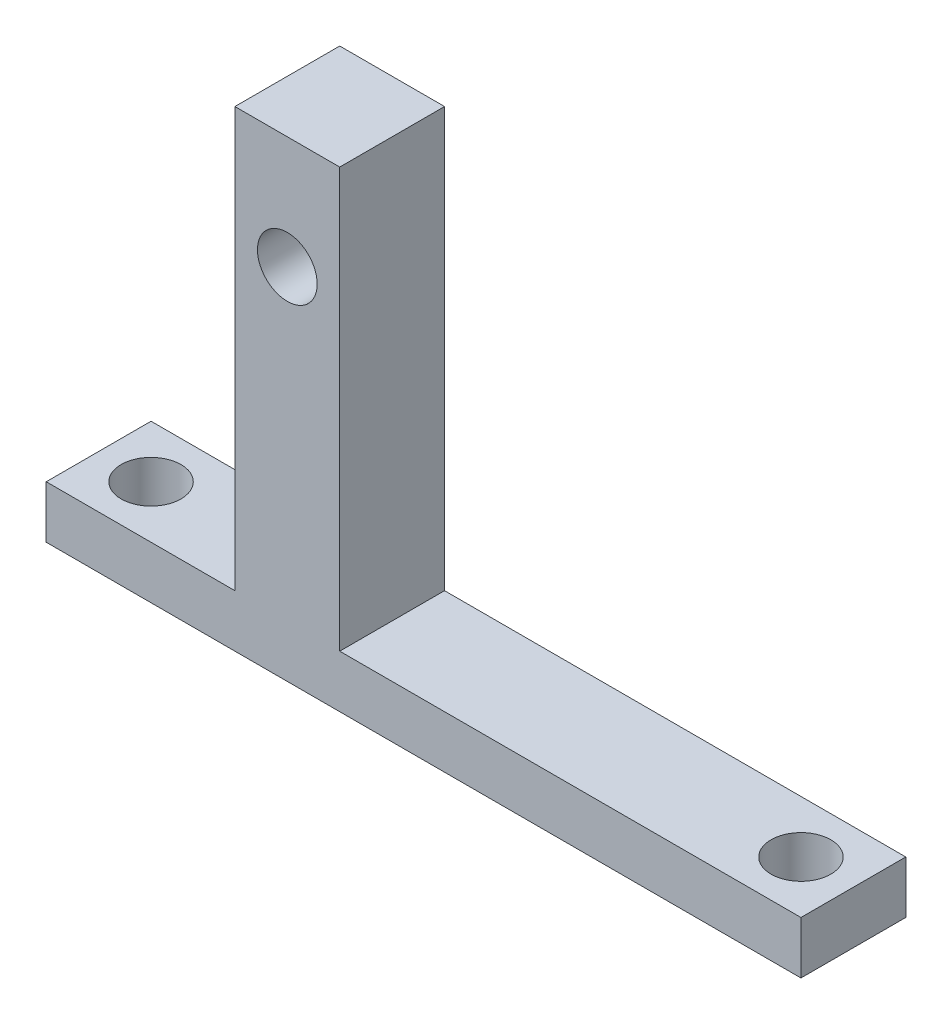
SolidWorks part; units mm, degrees
ref_plane "Front Plane" through (0, 0, 0) normal (0, 0, 1) x (1, 0, 0)
ref_plane "Top Plane" through (0, 0, 0) normal (0, 1, 0) x (1, 0, 0)
ref_plane "Right Plane" through (0, 0, 0) normal (1, 0, 0) x (0, 0, -1)
sketch "Sketch1" plane through (0, 0, 0) normal (0, 1, 0) x (1, 0, 0)
  line L1 (-24.6256, -25.05) -> (30.2384, -25.05)
  line L2 (-24.6256, -25.05) -> (-24.6256, -32.67)
  line L3 (-24.6256, -32.67) -> (30.2384, -32.67)
  line L4 (30.2384, -25.05) -> (30.2384, -32.67)
  dimension "D1" = 54.864
  dimension "D2" = 7.62
extrude "Boss-Extrude1" add sketch "Sketch1" along normal blind 3.81
sketch "Sketch2" plane through (0, 3.81, 0) normal (0, 1, 0) x (1, 0, 0)
  line L0 (30.2384, -25.05) -> (-24.6256, -25.05) construction
  line L1 (-24.6256, -25.05) -> (-24.6256, -32.67) construction
  line L3 (30.2384, -32.67) -> (30.2384, -25.05) construction
  circle A0 centre (-20.8156, -28.86) radius 2.1717
  circle A3 centre (26.4284, -28.86) radius 2.1717
  dimension "D1" = 3.81
  dimension "D7" = 3.81
  dimension "D2" = 3.81
  dimension "D8" = 3.81
extrude "Cut-Extrude2" cut sketch "Sketch2" against normal blind 3.81
sketch "Sketch3" plane through (0, 3.81, 0) normal (0, 1, 0) x (1, 0, 0)
  line L0 (-24.6256, -25.05) -> (-24.6256, -32.67) construction
  line L1 (-24.6256, -26.3171) -> (-18.2756, -26.3171)
  line L2 (-24.6256, -26.3171) -> (-24.6256, -32.67)
  line L3 (-24.6256, -32.67) -> (-18.2756, -32.67)
  line L4 (-18.2756, -26.3171) -> (-18.2756, -32.67)
  line L5 (-24.6256, -32.67) -> (30.2384, -32.67) construction
  line L6 (30.2384, -32.67) -> (30.2384, -25.05) construction
  line L7 (30.2384, -26.32) -> (23.8884, -26.32)
  line L8 (30.2384, -26.32) -> (30.2384, -32.67)
  line L9 (30.2384, -32.67) -> (23.8884, -32.67)
  line L10 (23.8884, -26.32) -> (23.8884, -32.67)
  dimension "D1" = 6.35
  dimension "D2" = 6.3528
  dimension "D3" = 6.35
  dimension "D4" = 6.35
sketch "Sketch5" plane through (0, 3.81, 0) normal (0, 1, 0) x (1, 0, 0)
  line L0 (30.2384, -25.05) -> (-24.6256, -25.05) construction
  line L1 (-10.9096, -25.05) -> (-3.2896, -25.05)
  line L2 (-10.9096, -25.05) -> (-10.9096, -32.67)
  line L3 (-10.9096, -32.67) -> (-3.2896, -32.67)
  line L4 (-3.2896, -25.05) -> (-3.2896, -32.67)
  line L5 (-24.6256, -32.67) -> (30.2384, -32.67) construction
  line L6 (-24.6256, -26.3171) -> (-24.6256, -32.67) construction
  line L7 (30.2384, -26.32) -> (30.2384, -32.67) construction
  dimension "D1" = 13.716
  dimension "D2" = 33.528
extrude "Boss-Extrude2" add sketch "Sketch5" along normal blind 30.48
sketch "Sketch6" plane through (0, 0, 32.67) normal (0, 0, 1) x (1, 0, 0)
  line L0 (-3.2896, 34.29) -> (-3.2896, 3.81) construction
  line L1 (-24.6256, 0) -> (30.2384, 0) construction
  circle A0 centre (-7.0996, 26.0985) radius 2.1717
  dimension "D1" = 3.81
  dimension "D2" = 26.0985
extrude "Cut-Extrude3" cut sketch "Sketch6" against normal blind 7.62
